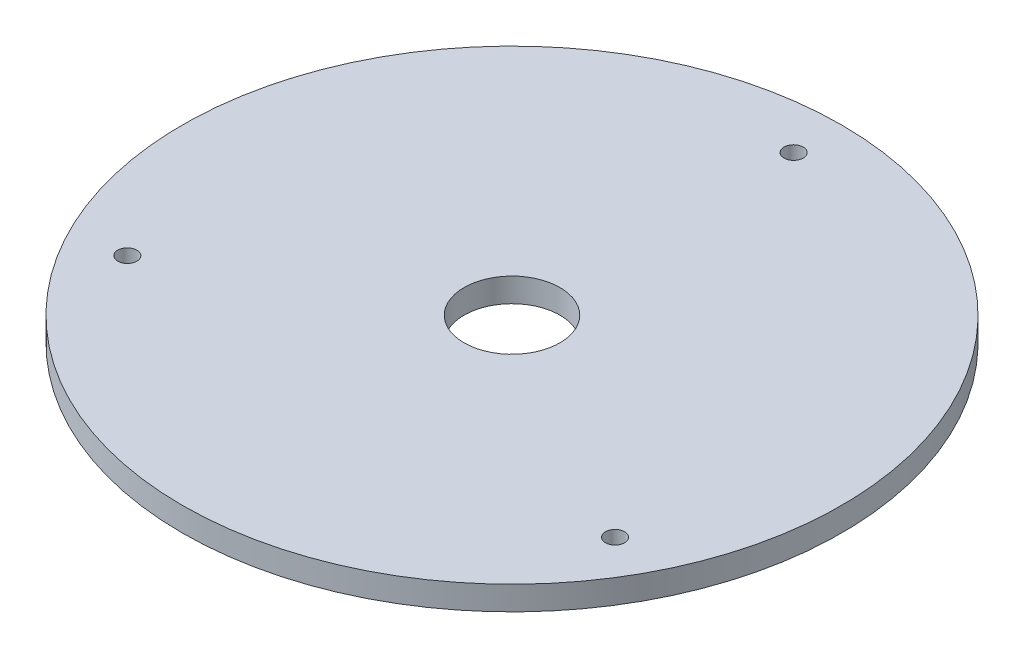
SolidWorks part; units mm, degrees
ref_plane "Piano frontale" through (0, 0, 0) normal (0, 0, 1) x (1, 0, 0)
ref_plane "Piano superiore" through (0, 0, 0) normal (0, 1, 0) x (1, 0, 0)
ref_plane "Piano destro" through (0, 0, 0) normal (1, 0, 0) x (0, 0, -1)
sketch "Schizzo1" plane through (0, 0, 0) normal (0, 1, 0) x (1, 0, 0)
  circle A0 centre (0, 0) radius 55
  dimension "D1" = 110
extrude "Estrusione-Estrusione1" add sketch "Schizzo1" along normal blind 4
sketch "Schizzo2" plane through (0, 4, 0) normal (0, 1, 0) x (1, 0, 0)
  line L0 (0, -49.6805) -> (0, 53.3455) construction
  circle A0 centre (0, 0) radius 8
  circle A1 centre (0, 47) radius 1.6
  circle A2 centre (40.7032, -23.5) radius 1.6
  circle A3 centre (-40.7032, -23.5) radius 1.6
  point P14 (0, 0)
  dimension "D1" = 16
  dimension "D3" = 3.2
  dimension "D2" = 47
  dimension "D4" = 3
extrude "Taglio-Estrusione1" cut sketch "Schizzo2" against normal through all
